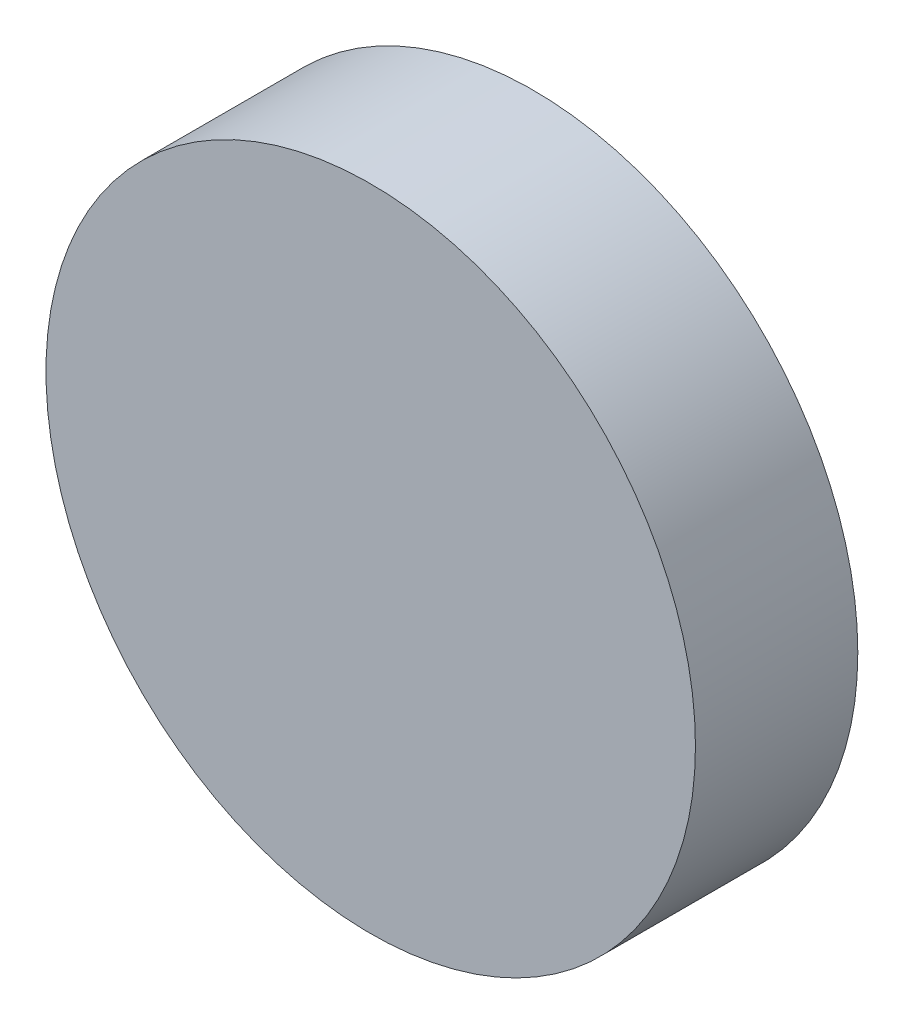
SolidWorks part; units mm, degrees
ref_plane "前视基准面" through (0, 0, 0) normal (0, 0, 1) x (1, 0, 0)
ref_plane "上视基准面" through (0, 0, 0) normal (0, 1, 0) x (1, 0, 0)
ref_plane "右视基准面" through (0, 0, 0) normal (1, 0, 0) x (0, 0, -1)
sketch "草图3" plane through (0, 0, 0) normal (0, 0, 1) x (1, 0, 0)
  circle A0 centre (0, 0) radius 10
extrude "凸台-拉伸1" add sketch "草图3" along normal blind 5
sketch "草图4" plane through (0, 0, 0) normal (0, 0, -1) x (-1, 0, 0)
  circle A0 centre (0, 0) radius 1
extrude "凸台-拉伸2" add sketch "草图4" along normal blind 5
